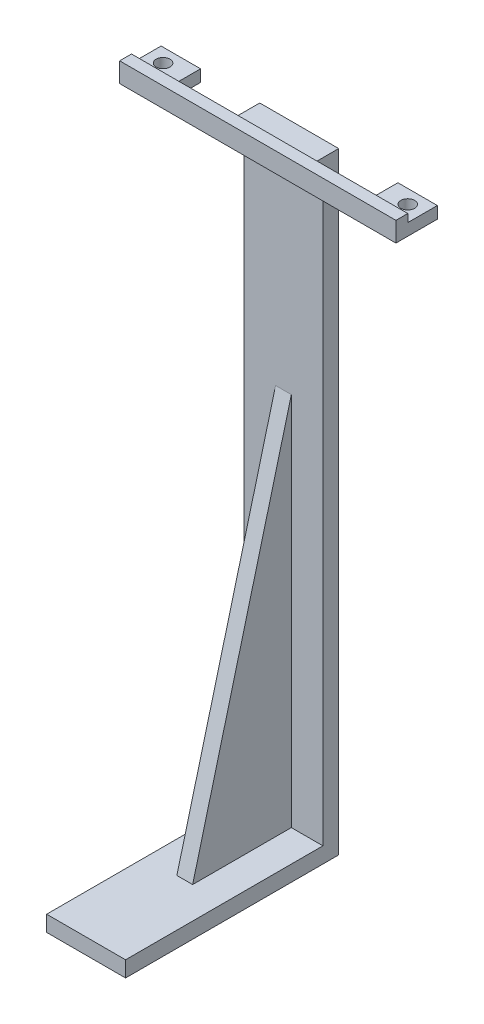
SolidWorks part; units mm, degrees
ref_plane "Front Plane" through (0, 0, 0) normal (0, 0, 1) x (1, 0, 0)
ref_plane "Top Plane" through (0, 0, 0) normal (0, 1, 0) x (1, 0, 0)
ref_plane "Right Plane" through (0, 0, 0) normal (1, 0, 0) x (0, 0, -1)
sketch "Sketch1" plane through (0, 0, 0) normal (0, 0, 1) x (1, 0, 0)
  line L1 (10, 77.5) -> (-10, 77.5)
  line L2 (10, 77.5) -> (10, -77.5)
  line L3 (10, -77.5) -> (-10, -77.5)
  line L4 (-10, 77.5) -> (-10, -77.5)
  line L5 (10, 77.5) -> (-10, -77.5) construction
  line L6 (10, -77.5) -> (-10, 77.5) construction
  point P0 (0, 0)
  dimension "D1" = 20
  dimension "D2" = 155
extrude "Boss-Extrude1" add sketch "Sketch1" along normal blind 4
sketch "Sketch2" plane through (0, 0, 4) normal (0, 0, 1) x (1, 0, 0)
  line L0 (10, -77.5) -> (10, 77.5) construction
  line L1 (-10, -77.5) -> (10, -77.5)
  line L2 (-10, -77.5) -> (-10, -73.5)
  line L3 (-10, -73.5) -> (10, -73.5)
  line L4 (10, -77.5) -> (10, -73.5)
  dimension "D1" = 4
extrude "Boss-Extrude3" add sketch "Sketch2" along normal blind 50 contours L3 L4 L1 L2
sketch "Sketch7" plane through (0, 0, 0) normal (1, 0, 0) x (0, 0, -1)
  line L0 (-29, -73.5) -> (-4, 21.5)
  line L1 (-54, -73.5) -> (-4, -73.5) construction
  line L2 (-4, -73.5) -> (-4, 77.5) construction
  dimension "D1" = 95
  dimension "D2" = 25
rib "Rib2" sketch "Sketch7" sketch "Sketch7" thickness 4 extrusion direction parallel to sketch draft on no parameters "D1"=4
sketch "Sketch8" plane through (0, 0, 4) normal (0, 0, 1) x (1, 0, 0)
  line L0 (-10, 77.5) -> (-10, -73.5) construction
  line L1 (10, 77.5) -> (-10, 77.5)
  line L2 (10, 77.5) -> (10, 74.5)
  line L3 (10, 74.5) -> (-10, 74.5)
  line L4 (-10, 77.5) -> (-10, 74.5)
  dimension "D1" = 3
extrude "Boss-Extrude4" add sketch "Sketch8" along normal blind 3.5
sketch "Sketch9" plane through (0, 0, 7.5) normal (0, 0, 1) x (1, 0, 0)
  line L1 (-35, 79.5) -> (35, 79.5)
  line L2 (-35, 79.5) -> (-35, 74.5)
  line L3 (-35, 74.5) -> (35, 74.5)
  line L4 (35, 79.5) -> (35, 74.5)
  line L5 (10, -73.5) -> (10, 74.5) construction
  line L7 (-10, 74.5) -> (10, 74.5) construction
  dimension "D1" = 70
  dimension "D2" = 25
  dimension "D3" = 5
extrude "Boss-Extrude6" add sketch "Sketch9" along normal blind 3
sketch "Sketch10" plane through (0, 0, 7.5) normal (0, 0, -1) x (-1, 0, 0)
  line L1 (35, 74.5) -> (25, 74.5)
  line L2 (35, 74.5) -> (35, 77.5)
  line L3 (35, 77.5) -> (25, 77.5)
  line L4 (25, 74.5) -> (25, 77.5)
  line L5 (-35, 74.5) -> (-25, 74.5)
  line L6 (-35, 74.5) -> (-35, 77.5)
  line L7 (-35, 77.5) -> (-25, 77.5)
  line L8 (-25, 74.5) -> (-25, 77.5)
  dimension "D1" = 10
  dimension "D2" = 3
  dimension "D3" = 10
  dimension "D4" = 3
extrude "Boss-Extrude7" add sketch "Sketch10" along normal blind 7.5
sketch "Sketch12" plane through (0, 77.5, 0) normal (0, 1, 0) x (1, 0, 0)
  line L1 (-35, -7.5) -> (-25, -7.5) construction
  line L2 (-35, 0) -> (-35, -7.5) construction
  line L3 (35, -7.5) -> (-35, -7.5) construction
  line L4 (35, 0) -> (35, -7.5) construction
  circle A0 centre (-31, -3.5) radius 1.75
  circle A1 centre (31, -3.5) radius 1.75
  dimension "D1" = 3.5
  dimension "D4" = 3.5
  dimension "D2" = 4
  dimension "D3" = 4
  dimension "D5" = 4
  dimension "D6" = 4
extrude "Cut-Extrude1" cut sketch "Sketch12" against normal blind 10
